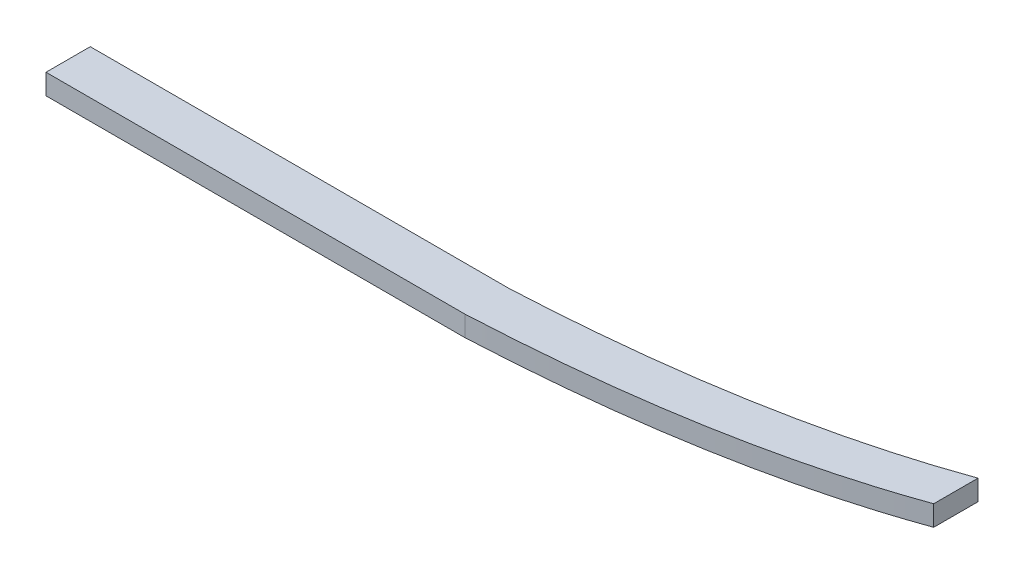
SolidWorks part; units mm, degrees
ref_plane "Front Plane" through (0, 0, 0) normal (0, 0, 1) x (1, 0, 0)
ref_plane "Top Plane" through (0, 0, 0) normal (0, 1, 0) x (1, 0, 0)
ref_plane "Right Plane" through (0, 0, 0) normal (1, 0, 0) x (0, 0, -1)
sketch "Sketch1" plane through (0, 0, 0) normal (0, 1, 0) x (1, 0, 0)
  line L0 (0, 0) -> (120, 0) construction
  line L1 (-66.0158, 0) -> (66.0158, 0) construction
  line L2 (0, 0) -> (61.5, 0)
  line L3 (0, 0) -> (0, 10.3) construction
  line L4 (0, -9.2418) -> (0, 9.2418) construction
  line L5 (0, 10.3) -> (120.0261, 10.3) construction
  line L6 (120.0261, 10.3) -> (120, 0) construction
  line L7 (120, 0) -> (0, 0) construction
  line L8 (0, 0) -> (0, 6.5)
  line L9 (0, 6.5) -> (61.5, 6.5)
  line L10 (120.0261, 10.3) -> (120.0288, 16.8032)
  spline S0 degree 2 poles (61.5, 0) (96.0799, 1.6899) (120.0261, 10.3) knots 0 0 0 1 1 1
  spline S1 degree 2 poles (61.5, 6.5) (96.0825, 8.1932) (120.0288, 16.8032) knots 0 0 0 1 1 1
  point P14 (61.5009, 6.5)
  dimension "D1" = 120
  dimension "D2" = 61.5
  dimension "D3" = 10.3
  dimension "D4" = 6.5
extrude "Boss-Extrude1" add sketch "Sketch1" along normal blind 3
